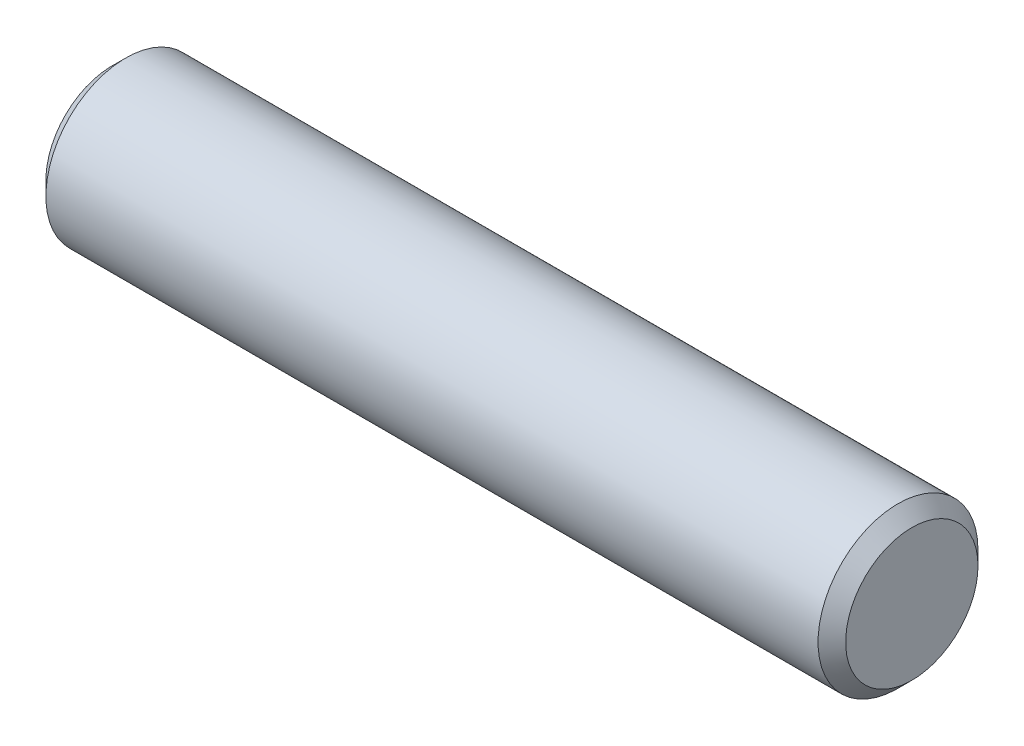
SolidWorks part; units mm, degrees
ref_plane "Plane1" through (0, 0, 0) normal (0, 0, 1) x (1, 0, 0)
ref_plane "Plane2" through (0, 0, 0) normal (0, 1, 0) x (1, 0, 0)
ref_plane "Plane3" through (0, 0, 0) normal (1, 0, 0) x (0, 0, -1)
sketch "BodySke" plane through (0, 0, 0) normal (0, 0, 1) x (1, 0, 0)
  line L0 (33.381, 15.875) -> (33.381, -6.35) construction
  line L1 (1.25, 15.875) -> (1.25, -3.175) construction
  line L2 (40, 6.35) -> (40, 3.175) construction
  line L10 (0, 4) -> (40, 4)
  line L12 (40, 4) -> (40, 0)
  line L13 (40, 0) -> (0, 0)
  line L14 (-3.175, 0) -> (107.95, 0) construction
  line L18 (0, 4) -> (0, 0)
  dimension "Diameter" = 8
  dimension "Minor_dia" = 6.619
  dimension "Length" = 40
  dimension "Advance" = 1.25
  dimension "Thread_max" = 40
revolve "BaseBody" add sketch "BodySke" angle 360 about L14
cosmetic thread "ThreadCosmetic" [suppressed] parameters "Thread_minor"=6.619
chamfer "Chamfer1" distance 0.6905 angle 45 2 edges at (0, 0, 4) (40, 0, 4)
sketch "ThdSchSke" plane through (0, 0, 0) normal (0, 0, 1) x (1, 0, 0)
  line L0 (0.4835, -3.3095) -> (0, -4)
  line L1 (0.4835, -3.3095) -> (0.967, -4)
  line L2 (0.967, -4) -> (0.967, -5)
  line L3 (-3.175, 0) -> (5.1513, 0) construction
  line L4 (0, 4) -> (0, -4) construction
  line L5 (0.967, -5) -> (0, -5)
  line L6 (0, -5) -> (0, -4)
  dimension "Thread_minor" = 6.619
  dimension "Diameter" = 8
  dimension "SideAngle" = 55
  dimension "VeeAngle" = 70
  dimension "Overcut" = 10
revolve "ThreadSchematic" [suppressed] cut sketch "ThdSchSke" angle 360 about L3
pattern_linear "ThdSchPat" [suppressed]
equation "\"Thread_minor@ThreadCosmetic\" = \"Minor_dia@BodySke\""
equation "\"Chamfer@Chamfer1\" =  ( \"Diameter@BodySke\" - \"Minor_dia@BodySke\" ) / 2"
equation "\"Thread_minor@ThdSchSke\" = \"Minor_dia@BodySke\""
equation "\"Diameter@ThdSchSke\" = \"Diameter@BodySke\""
equation "\"Overcut@ThdSchSke\" = \"Diameter@BodySke\" * 1.25"
equation "\"Num_threads@ThdSchPat\" = int( (\"Thread_max@BodySke\" - \"Advance@BodySke\" ) / \"Advance@BodySke\" + 0.999 ) + 1"
equation "\"Advance@ThdSchPat\" = \"Thread_max@BodySke\" /  ( \"Num_threads@ThdSchPat\" - 1 ) 'relax it"
equation "\"Num_threads@ThdSchPat\" = \"Num_threads@ThdSchPat\" - sgn( \"Num_threads@ThdSchPat\" - 1 ) '---chamfered tips only---"
